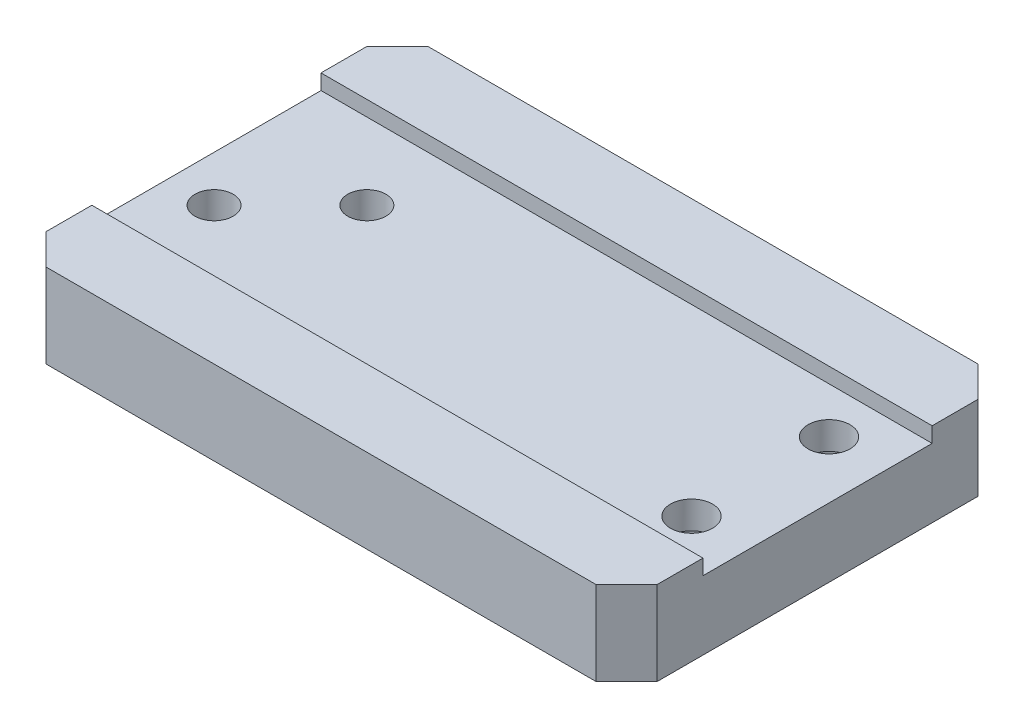
SolidWorks part; units mm, degrees
material "Ferro fundido cinza"
ref_plane "Plano frontal" through (0, 0, 0) normal (0, 0, 1) x (1, 0, 0)
ref_plane "Plano superior" through (0, 0, 0) normal (0, 1, 0) x (1, 0, 0)
ref_plane "Plano direito" through (0, 0, 0) normal (1, 0, 0) x (0, 0, -1)
sketch "Esboço1" plane through (0, 0, 0) normal (0, 1, 0) x (1, 0, 0)
  line L0 (0, 0) -> (0, -25)
  line L1 (0, -25) -> (80, -25)
  line L2 (80, -25) -> (80, 25)
  line L3 (80, 25) -> (0, 25)
  line L4 (0, 25) -> (0, 0)
  dimension "D1" = 25
  dimension "D2" = 25
  dimension "D3" = 80
extrude "Ressalto-extrusão1" add sketch "Esboço1" along normal blind 11
sketch "Esboço2" plane through (0, 11, 0) normal (0, 1, 0) x (1, 0, 0)
  line L0 (0, 25) -> (0, -25) construction
  line L1 (0, 15) -> (80, 15)
  line L2 (0, 15) -> (0, -15)
  line L3 (0, -15) -> (80, -15)
  line L4 (80, 15) -> (80, -15)
  line L5 (80, -25) -> (80, 25) construction
  dimension "D1" = 30
  dimension "D2" = 10
extrude "Corte-extrusão1" cut sketch "Esboço2" against normal blind 2
sketch "Esboço4" plane through (0, 9, 0) normal (0, 1, 0) x (1, 0, 0)
  circle A0 centre (16, 5) radius 2.5
  circle A1 centre (6, -5) radius 2.5
  dimension "D1" = 5
  dimension "D2" = 5
  dimension "D3" = 6
  dimension "D5" = 10
  dimension "D4" = 16
  dimension "D6" = 5
extrude "Corte-extrusão2" cut sketch "Esboço4" against normal through all
sketch "Esboço5" plane through (0, 9, 0) normal (0, 1, 0) x (1, 0, 0)
  line L0 (80, -15) -> (80, 15) construction
  line L1 (80, 15) -> (0, 15) construction
  circle A0 centre (72.5, 9) radius 2.75
  circle A1 centre (72.5, -9) radius 2.75
  dimension "D1" = 5.5
  dimension "D2" = 5.5
  dimension "D3" = 18
  dimension "D4" = 7.5
  dimension "D5" = 7.5
  dimension "D6" = 6
extrude "Corte-extrusão3" cut sketch "Esboço5" against normal through all
chamfer "Chanfro2" distance 4 angle 45 4 edges at (80, 5.5, -25) (80, 5.5, 25) (0, 5.5, -25) (0, 5.5, 25)
sketch "Esboço7" plane through (0, 0, 0) normal (0, -1, 0) x (1, 0, 0)
  circle A0 centre (72.5, 9) radius 4.75
  circle A1 centre (72.5, -9) radius 4.75
  dimension "D1" = 9.5
  dimension "D2" = 9.5
extrude "Corte-extrusão6" cut sketch "Esboço7" against normal blind 5.4
